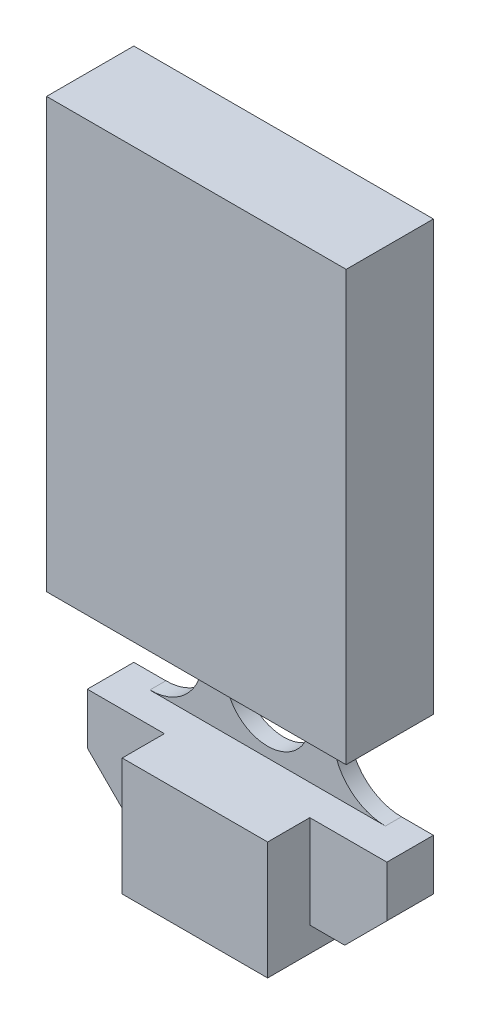
SolidWorks part; units mm, degrees
ref_plane "Front Plane" through (0, 0, 0) normal (0, 0, 1) x (1, 0, 0)
ref_plane "Top Plane" through (0, 0, 0) normal (0, 1, 0) x (1, 0, 0)
ref_plane "Right Plane" through (0, 0, 0) normal (1, 0, 0) x (0, 0, -1)
sketch "Sketch1" plane through (0, 0, 0) normal (0, 0, 1) x (1, 0, 0)
  line L1 (0, 0) -> (20.6, 0)
  line L2 (0, 0) -> (0, 43.1)
  line L3 (0, 43.1) -> (20.6, 43.1)
  line L4 (20.6, 0) -> (20.6, 43.1)
  dimension "D1" = 43.1
  dimension "D2" = 20.6
extrude "Boss-Extrude1" add sketch "Sketch1" along normal blind 1.1
sketch "Sketch2" plane through (0, 0, 1.1) normal (0, 0, 1) x (1, 0, 0)
  line L0 (20.6, 0) -> (20.6, 43.1) construction
  line L1 (0, 43.1) -> (20.6, 43.1)
  line L2 (0, 43.1) -> (0, 13.6)
  line L3 (0, 13.6) -> (20.6, 13.6)
  line L4 (20.6, 43.1) -> (20.6, 13.6)
  dimension "D1" = 29.5
extrude "Boss-Extrude2" add sketch "Sketch2" along normal blind 4.9
sketch "Sketch3" plane through (0, 0, 1.1) normal (0, 0, 1) x (1, 0, 0)
  line L0 (10.3, 43.1) -> (10.3, 0) construction
  line L1 (20.6, 43.1) -> (0, 43.1) construction
  line L2 (0, 0) -> (20.6, 0) construction
  line L3 (0, 10) -> (20.6, 10) construction
  line L4 (0, 13.6) -> (0, 0) construction
  line L5 (20.6, 0) -> (20.6, 13.6) construction
  line L6 (0, 13.6) -> (2.2, 13.6)
  line L7 (0, 13.6) -> (20.6, 13.6) construction
  line L8 (2.2, 6.4) -> (0, 6.4)
  line L9 (0, 6.4) -> (0, 13.6)
  line L10 (20.6, 13.6) -> (18.4, 13.6)
  line L11 (18.4, 6.4) -> (20.6, 6.4)
  line L12 (20.6, 6.4) -> (20.6, 13.6)
  circle A0 centre (10.3, 10) radius 2.9
  arc A1 (2.2, 13.6) -> (2.2, 6.4) centre (2.2, 10) cw
  arc A2 (18.4, 13.6) -> (18.4, 6.4) centre (18.4, 10) ccw
  dimension "D1" = 5.8
  dimension "D3" = 16.2
  dimension "D2" = 7.2
  dimension "D4" = 2.2
extrude "Cut-Extrude1" cut sketch "Sketch3" against normal blind 4.9
sketch "Sketch4" plane through (0, 0, 1.1) normal (0, 0, 1) x (1, 0, 0)
  line L0 (10.3, 0) -> (10.3, 43.1) construction
  line L1 (5.3, -1.7) -> (15.3, -1.7)
  line L2 (5.3, -1.7) -> (5.3, 6.4)
  line L3 (5.3, 6.4) -> (15.3, 6.4)
  line L4 (15.3, -1.7) -> (15.3, 6.4)
  line L5 (0, 0) -> (20.6, 0) construction
  line L6 (20.6, 43.1) -> (0, 43.1) construction
  line L7 (0, 6.4) -> (20.6, 6.4) construction
  dimension "D1" = 8.1
  dimension "D2" = 10
  dimension "D3" = 5
extrude "Boss-Extrude3" add sketch "Sketch4" along normal blind 5
sketch "Sketch5" plane through (0, 0, 1.1) normal (0, 0, 1) x (1, 0, 0)
  line L1 (0, 6.4) -> (20.6, 6.4)
  line L2 (0, 6.4) -> (0, 0)
  line L3 (0, 0) -> (20.6, 0)
  line L4 (20.6, 6.4) -> (20.6, 0)
extrude "Boss-Extrude4" add sketch "Sketch5" along normal blind 2.1
sketch "Sketch6" plane through (0, 0, 3.2) normal (0, 0, 1) x (1, 0, 0)
  line L0 (0, 0) -> (0, 2.9)
  line L1 (0, 6.4) -> (0, 0) construction
  line L2 (0, 2.9) -> (2.9, 0)
  line L3 (0, 0) -> (5.3, 0) construction
  line L4 (2.9, 0) -> (0, 0)
  line L5 (20.6, 0) -> (20.6, 2.9)
  line L6 (20.6, 0) -> (20.6, 6.4) construction
  line L7 (20.6, 2.9) -> (17.7, 0)
  line L8 (15.3, 0) -> (20.6, 0) construction
  line L9 (17.7, 0) -> (20.6, 0)
  line L10 (5.3, 6.4) -> (0, 6.4) construction
  line L11 (0, 2.9) -> (20.6, 2.9) construction
  dimension "D1" = 45
  dimension "D2" = 3.5
extrude "Cut-Extrude2" cut sketch "Sketch6" against normal through all
